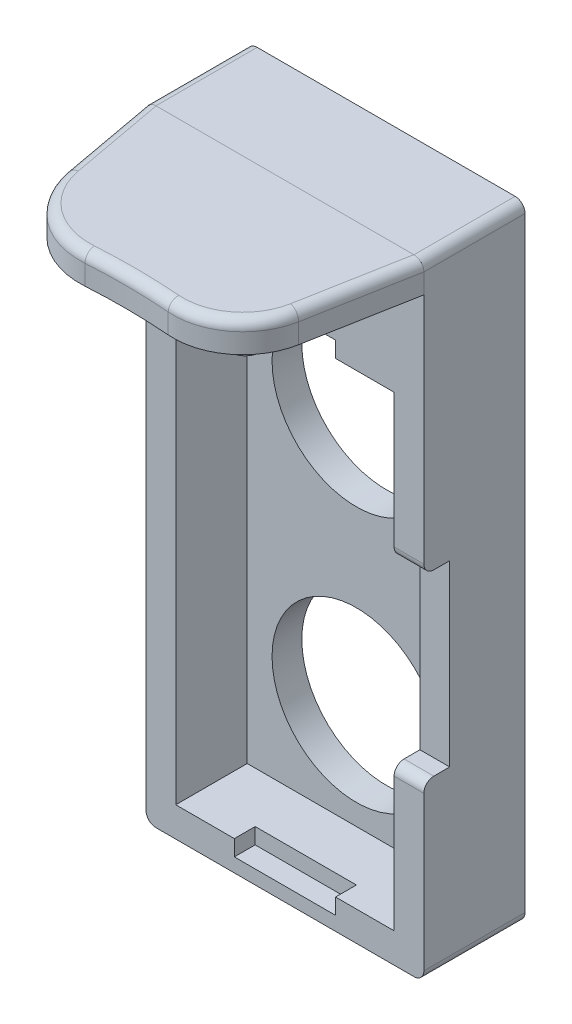
SolidWorks part; units mm, degrees
ref_plane "Front Plane" through (0, 0, 0) normal (0, 0, 1) x (1, 0, 0)
ref_plane "Top Plane" through (0, 0, 0) normal (0, 1, 0) x (1, 0, 0)
ref_plane "Right Plane" through (0, 0, 0) normal (1, 0, 0) x (0, 0, -1)
sketch "Sketch2" plane through (0, 0, 0) normal (0, 0, 1) x (1, 0, 0)
  line L0 (0, 23.5) -> (0, -23.5) construction
  line L1 (-11, -23.5) -> (11, -23.5)
  line L2 (-11, -23.5) -> (-11, 23.5)
  line L3 (-11, 23.5) -> (11, 23.5)
  line L4 (11, -23.5) -> (11, 23.5)
  line L5 (-11, -23.5) -> (-7.7117, -16.4749) construction
  line L6 (-11, 23.5) -> (-7.7117, 16.4749) construction
  line L7 (-11, 0) -> (11, 0) construction
  line L8 (-2.1945, 4.6882) -> (2.1945, -4.6882) construction
  line L9 (-14, -26.5) -> (14, -26.5)
  line L10 (-14, -26.5) -> (-14, 26.5)
  line L11 (-14, 26.5) -> (14, 26.5)
  line L12 (14, -26.5) -> (14, 26.5)
  line L13 (-14, -26.5) -> (-8.1284, -15.3859) construction
  line L14 (-14, 26.5) -> (-8.1284, 15.3859) construction
  line L15 (-2.5277, 4.7845) -> (2.5277, -4.7845) construction
  line L16 (7.7117, 16.4749) -> (11, 23.5) construction
  line L17 (8.1284, 15.3859) -> (14, 26.5) construction
  line L18 (-2.1945, -4.6882) -> (2.1945, 4.6882) construction
  line L19 (-2.5277, -4.7845) -> (2.5277, 4.7845) construction
  line L20 (7.7117, -16.4749) -> (11, -23.5) construction
  line L21 (8.1284, -15.3859) -> (14, -26.5) construction
  circle A0 centre (0, 12.9) radius 8.5
  circle A1 centre (0, -12.9) radius 8.5
  point P0 (0, 0)
  point P10 (0, 0)
  dimension "D3" = 17
  dimension "D1" = 47
  dimension "D2" = 22
  dimension "D4" = 12.9
  dimension "D5" = 53
  dimension "D6" = 28
extrude "Boss-Extrude1" add sketch "Sketch2" along normal blind 3 contours L9 L12 L11 L10 L4 L1 L2 L3 | L1 L4 L3 L2 A0 A1
sketch "Sketch3" plane through (0, 0, 3) normal (0, 0, 1) x (1, 0, 0)
  line L1 (-14, -26.5) -> (14, -26.5)
  line L2 (-14, -26.5) -> (-14, 26.5)
  line L3 (-14, 26.5) -> (14, 26.5)
  line L4 (14, -26.5) -> (14, 26.5)
  line L5 (-14, -26.5) -> (14, 26.5) construction
  line L6 (-14, 26.5) -> (14, -26.5) construction
  point P0 (0, 0)
extrude "Extrude-Thin1" add sketch "Sketch3" along normal blind 7.2 thin thin type one direction reverse wall 3
sketch "Sketch4" plane through (0, 0, 10.2) normal (0, 0, 1) x (1, 0, 0)
  line L4 (0, 0) -> (14, 0) construction
  line L5 (14, -26.5) -> (14, 26.5) construction
  line L7 (11, -23.5) -> (11, 23.5) construction
  line L8 (8, -9) -> (14, -9)
  line L9 (8, -9) -> (8, 9)
  line L10 (8, 9) -> (14, 9)
  line L11 (14, -9) -> (14, 9)
  line L12 (8, -9) -> (14, 9) construction
  line L13 (8, 9) -> (14, -9) construction
  point P4 (11, 0)
  dimension "D1" = 18
extrude "Cut-Extrude1" cut sketch "Sketch4" against normal blind 2.6
sketch "Sketch5" plane through (0, 0, 10.2) normal (0, 0, 1) x (1, 0, 0)
  line L0 (-11, 23.5) -> (11, 23.5) construction
  line L1 (-5.1, 23.5) -> (5.1, 23.5)
  line L2 (-5.1, 23.5) -> (-5.1, 25.1)
  line L3 (-5.1, 25.1) -> (5.1, 25.1)
  line L4 (5.1, 23.5) -> (5.1, 25.1)
  line L5 (0, 23.5) -> (0, -23.5) construction
  line L6 (-11, 0) -> (11, 0) construction
  line L7 (-11, 0) -> (11, 0)
  line L8 (-5.1, -25.1) -> (5.1, -25.1)
  line L9 (5.1, -23.5) -> (5.1, -25.1)
  line L10 (-5.1, -23.5) -> (5.1, -23.5)
  line L11 (-5.1, -23.5) -> (-5.1, -25.1)
  line M14 (11, -23.5) -> (-11, -23.5)
  line M16 (-11, 23.5) -> (11, 23.5)
  dimension "D1" = 10.2
  dimension "D2" = 5.1
  dimension "D3" = 1.6
extrude "Cut-Extrude2" cut sketch "Sketch5" against normal blind 2.1 contours L4 L3 L2 M16 | L11 L8 L9 M14
sketch "Sketch6" plane through (0, 26.5, 0) normal (0, 1, 0) x (1, 0, 0)
  line L1 (-14, -10.2) -> (14, -10.2)
  line L2 (-14, -10.2) -> (-14, 0)
  line L3 (-14, 0) -> (14, 0)
  line L4 (14, -10.2) -> (14, 0)
extrude "Boss-Extrude2" add sketch "Sketch6" along normal blind 10
sketch "Sketch7" plane through (0, 36.5, 0) normal (0, 1, 0) x (1, 0, 0)
  line L0 (0, 0) -> (0, -145.3865) construction
  line L1 (-14, -10.2) -> (14, -10.2) construction
  line L2 (0, -86.4) -> (14, -10.2)
  line L3 (14, -10.2) -> (-14, -10.2)
  line L4 (-14, -10.2) -> (0, -86.4)
  line L6 (0, -10.2) -> (6, -10.2)
  line L7 (0, -10.2) -> (0, -20.2)
  line L8 (0, -20.2) -> (6, -20.2)
  line L9 (6, -10.2) -> (6, -20.2)
  circle A0 centre (0, -86.4) radius 76.2
  circle A1 centre (0, -86.4) radius 60
  circle A2 centre (6, -20.2) radius 1.5875
  circle A3 centre (-6, -20.2) radius 1.5875
  line M14 (-14, -10.2) -> (14, -10.2)
  dimension "D1" = 152.4
  dimension "D2" = 10
  dimension "D4" = 120
  dimension "D5" = 3.175
  dimension "D3" = 6
extrude "Boss-Extrude3" add sketch "Sketch7" against normal blind 3 separate body contours A0 L4 M14 | L0 L7 A0 L4 A1 A3 | L8 L0 A1 L2 A0 L9 A2 | A0 L2 L9 M14 | A2 L9 A0 L7 L8 | A3 | L8 A2 L9 | L9 A2 L8 | A0 L9 L3
sketch "Sketch8" plane through (0, 33.5, 0) normal (0, -1, 0) x (1, 0, 0)
  line L3 (14, 10.2) -> (0, 86.4)
  line L4 (14, 10.2) -> (-14, 10.2)
  line L5 (14, 0) -> (14, 10.2)
  line L6 (-14, 0) -> (14, 0)
  line L7 (-14, 10.2) -> (-14, 0)
  line L8 (14, 10.2) -> (-14, 10.2)
  line L9 (14, 0) -> (14, 10.2)
  line L10 (-14, 0) -> (14, 0)
  line L11 (-14, 10.2) -> (-14, 0)
  line L12 (-14, 10.2) -> (14, 10.2)
  line L13 (0, 86.4) -> (-14, 10.2)
  line L14 (14, 10.2) -> (0, 86.4)
  line L15 (-14, 10.2) -> (14, 10.2)
  line L16 (0, 86.4) -> (-14, 10.2)
  line L18 (0, 10.2) -> (6, 10.2)
  line L19 (0, 20.2) -> (0, 10.2)
  line L20 (6, 20.2) -> (0, 20.2)
  line L21 (6, 10.2) -> (6, 20.2)
  line L22 (0, 10.2) -> (6, 10.2)
  line L23 (0, 20.2) -> (0, 10.2)
  line L24 (6, 20.2) -> (0, 20.2)
  line L25 (6, 10.2) -> (6, 20.2)
  circle A1 centre (6, 20.2) radius 1.5875
  circle A2 centre (6, 20.2) radius 1.5875
  circle A3 centre (0, 86.4) radius 60
  circle A4 centre (0, 86.4) radius 60
  circle A5 centre (0, 86.4) radius 76.2
  circle A6 centre (0, 86.4) radius 76.2
  circle A7 centre (-6, 20.2) radius 1.5875
  circle A8 centre (-6, 20.2) radius 1.5875
  dimension "D1" = 0
  dimension "D2" = 0
  dimension "D3" = 0
  dimension "D4" = 0
  dimension "D5" = 0
  dimension "D6" = 0
  dimension "D7" = 0
extrude "Boss-Extrude4" add sketch "Sketch8" along normal blind 3.2 contours A8 | L25 A2 L24 | L24 A2 L25
fillet "Fillet1" radius 8 1 edges at (-10.8421, 35, 27.3877)
fillet "Fillet2" radius 7 1 edges at (10.8421, 35, 27.3877)
fillet "Fillet3" radius 1 5 edges at (-13.1012, 36.5, 15.0919) (13.0204, 36.5, 15.5318) (9.4259, 36.5, 25.1456) (0.3975, 36.5, 26.4013) (-9.2558, 36.5, 24.8451)
fillet "Fillet4" radius 1 6 edges at (12.5, -9, 10.2) (12.5, 9, 10.2) (14, -26.5, 5.1) (-14, -26.5, 5.1) (14, 36.5, 5.1) (-14, 36.5, 5.1)
